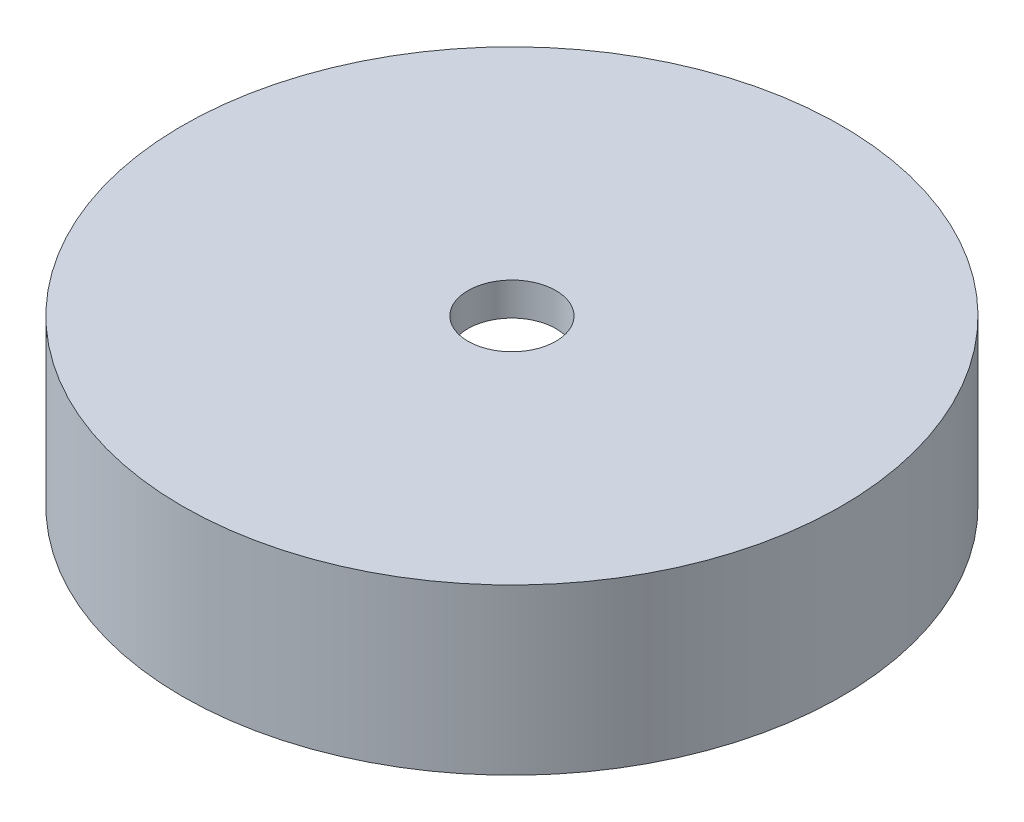
SolidWorks part; units mm, degrees
ref_plane "前视基准面" through (0, 0, 0) normal (0, 0, 1) x (1, 0, 0)
ref_plane "上视基准面" through (0, 0, 0) normal (0, 1, 0) x (1, 0, 0)
ref_plane "右视基准面" through (0, 0, 0) normal (1, 0, 0) x (0, 0, -1)
sketch "草图1" plane through (0, 0, 0) normal (0, 1, 0) x (1, 0, 0)
  circle A0 centre (0, 0) radius 30
extrude "凸台-拉伸1" add sketch "草图1" along normal blind 15
sketch "草图2" plane through (0, 0, 0) normal (0, 1, 0) x (1, 0, 0)
  circle A0 centre (0, 0) radius 25
extrude "切除-拉伸1" cut sketch "草图2" along normal blind 12
ref_plane "基准面1" through (0, 15, 0) normal (0, 1, 0) x (1, 0, 0)
sketch "草图3" plane through (0, 15, 0) normal (0, 1, 0) x (1, 0, 0)
  circle A0 centre (0, 0) radius 4
extrude "切除-拉伸2" cut sketch "草图3" against normal mid plane 122
